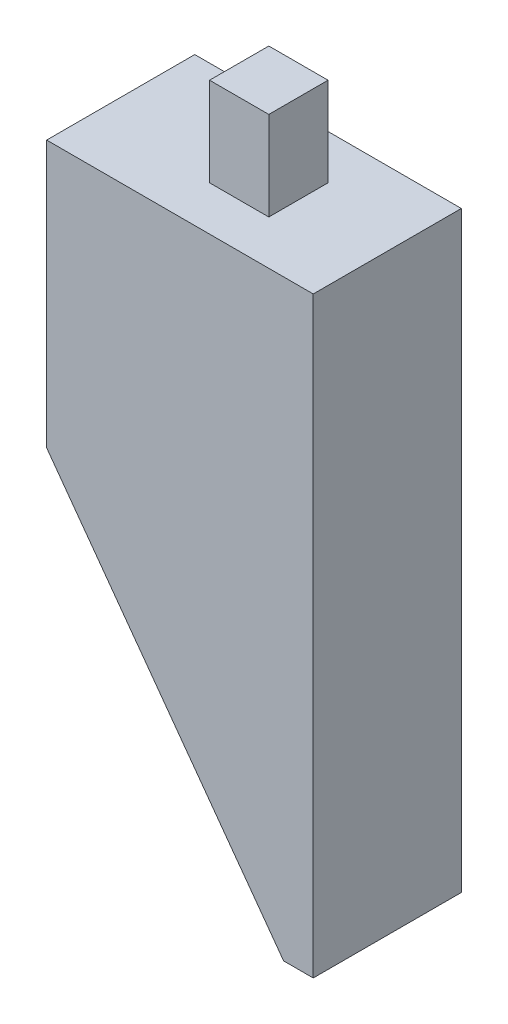
SolidWorks part; units mm, degrees
ref_plane "Alzado" through (0, 0, 0) normal (0, 0, 1) x (1, 0, 0)
ref_plane "Planta" through (0, 0, 0) normal (0, 1, 0) x (1, 0, 0)
ref_plane "Vista lateral" through (0, 0, 0) normal (1, 0, 0) x (0, 0, -1)
sketch "Croquis2" plane through (0, 0, 0) normal (0, 0, 1) x (1, 0, 0)
  line L0 (0, 200) -> (0, 110)
  line L1 (0, 110) -> (80, 0)
  line L2 (80, 0) -> (90, 0)
  line L3 (90, 0) -> (90, 200)
  line L4 (90, 200) -> (0, 200)
  dimension "D1" = 200
  dimension "D2" = 90
  dimension "D3" = 10
  dimension "D4" = 90
extrude "Saliente-Extruir3" add sketch "Croquis2" along normal blind 50
sketch "Croquis3" plane through (0, 200, 0) normal (0, 1, 0) x (1, 0, 0)
  line L1 (40, -15) -> (60, -15)
  line L2 (40, -15) -> (40, -35)
  line L3 (40, -35) -> (60, -35)
  line L4 (60, -15) -> (60, -35)
  line L5 (90, 0) -> (0, 0) construction
  line L7 (0, -50) -> (0, 0) construction
  point P4 (40, -25)
  point P7 (50, -15)
  dimension "D1" = 25
  dimension "D2" = 20
  dimension "D3" = 20
  dimension "D4" = 50
extrude "Saliente-Extruir4" add sketch "Croquis3" along normal blind 30
